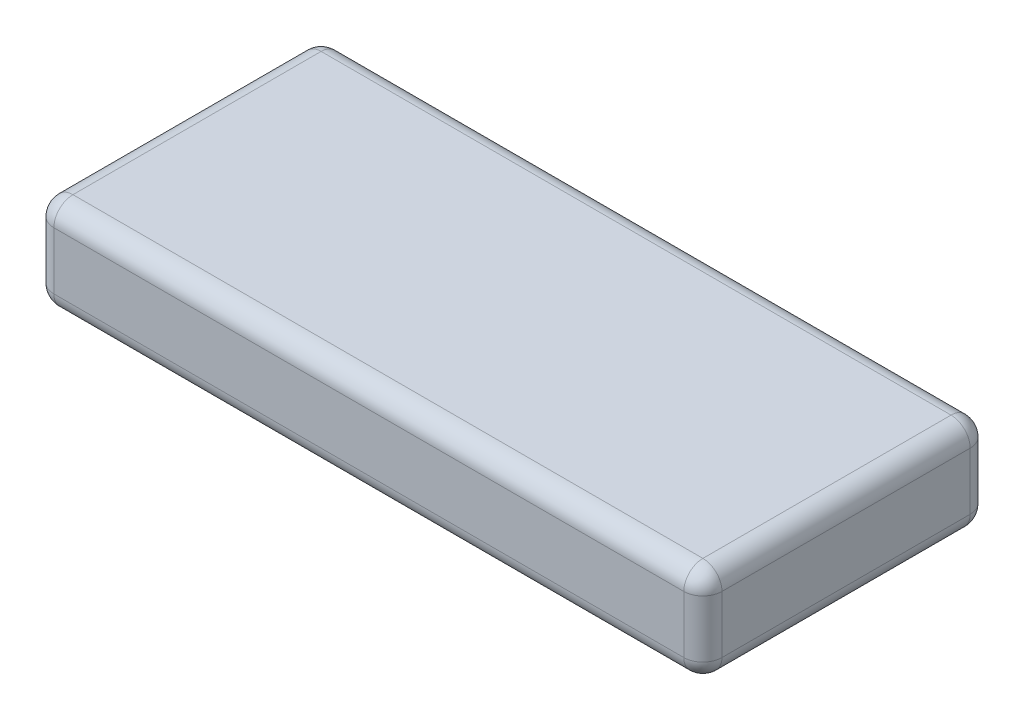
SolidWorks part; units mm, degrees
ref_plane "Front Plane" through (0, 0, 0) normal (0, 0, 1) x (1, 0, 0)
ref_plane "Top Plane" through (0, 0, 0) normal (0, 1, 0) x (1, 0, 0)
ref_plane "Right Plane" through (0, 0, 0) normal (1, 0, 0) x (0, 0, -1)
sketch "Sketch1" plane through (0, 0, 0) normal (0, 1, 0) x (1, 0, 0)
  line L1 (-35, 15) -> (35, 15)
  line L2 (-35, 15) -> (-35, -15)
  line L3 (-35, -15) -> (35, -15)
  line L4 (35, 15) -> (35, -15)
  line L5 (-35, 15) -> (35, -15) construction
  line L6 (-35, -15) -> (35, 15) construction
  point P0 (0, 0)
  dimension "D1" = 70
  dimension "D2" = 30
extrude "Boss-Extrude1" add sketch "Sketch1" along normal blind 10
fillet "Fillet1" radius 2 12 edges at (35, 5, 15) (35, 10, 0) (35, 5, -15) (35, 0, 0) (-35, 5, -15) (-35, 10, 0) (-35, 5, 15) (-35, 0, 0) (0, 10, -15) (0, 0, -15) (0, 10, 15) (0, 0, 15)
